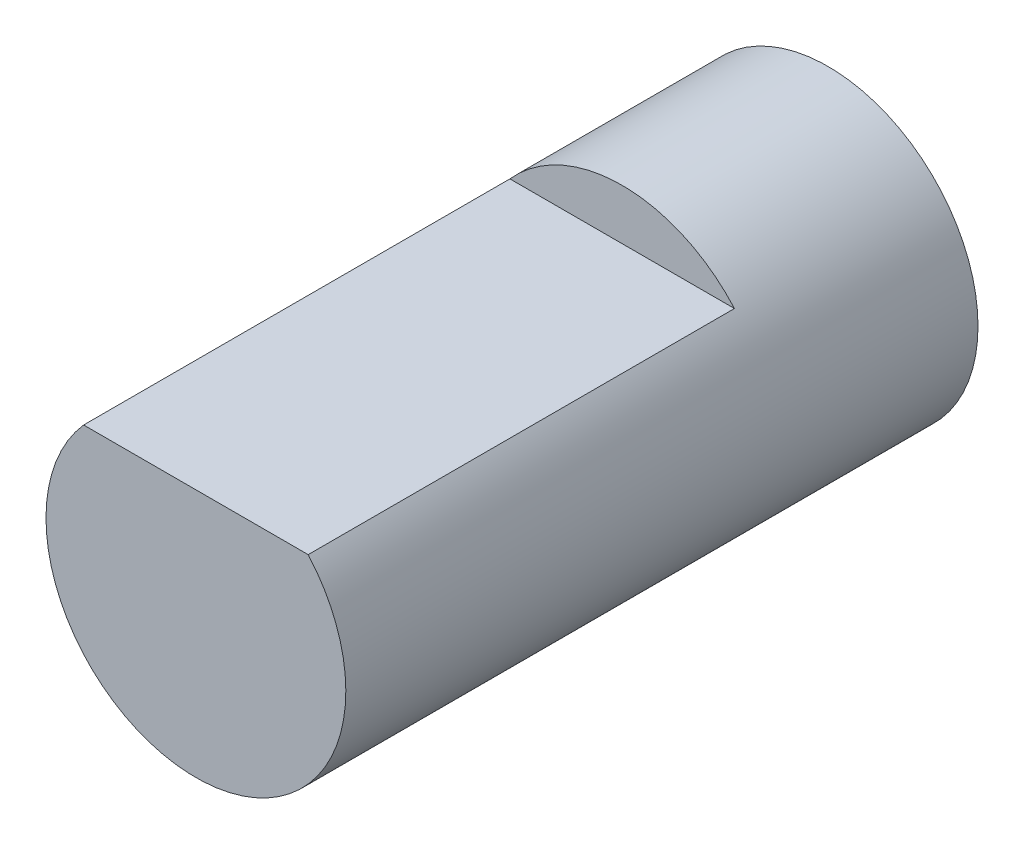
SolidWorks part; units mm, degrees
ref_plane "Front Plane" through (0, 0, 0) normal (0, 0, 1) x (1, 0, 0)
ref_plane "Top Plane" through (0, 0, 0) normal (0, 1, 0) x (1, 0, 0)
ref_plane "Right Plane" through (0, 0, 0) normal (1, 0, 0) x (0, 0, -1)
sketch "Sketch1" plane through (0, 0, 0) normal (0, 0, 1) x (1, 0, 0)
  circle A0 centre (0, 0) radius 4.15
  dimension "D1" = 8.3
extrude "Boss-Extrude1" add sketch "Sketch1" along normal blind 17.5
sketch "Sketch3" plane through (0, 0, 17.5) normal (0, 0, 1) x (1, 0, 0)
  line L0 (0, -4.15) -> (0, 2.75)
  line L1 (-2.2574, 2.75) -> (5.4038, 2.75)
  line L2 (5.4038, 2.75) -> (5.4038, 6.179)
  line L3 (5.4038, 6.179) -> (-6.3444, 6.179)
  line L4 (-6.3444, 6.179) -> (-6.3444, 2.75)
  line L5 (-6.3444, 2.75) -> (-2.2574, 2.75)
  circle A0 centre (0, 0) radius 4.15 construction
  circle M2 centre (0, 0) radius 4.15
  dimension "D1" = 6.9
extrude "Cut-Extrude2" cut sketch "Sketch3" against normal blind 11.8 contours L4 L5 L1 L2 L3 M2 | L5 L1 M2
